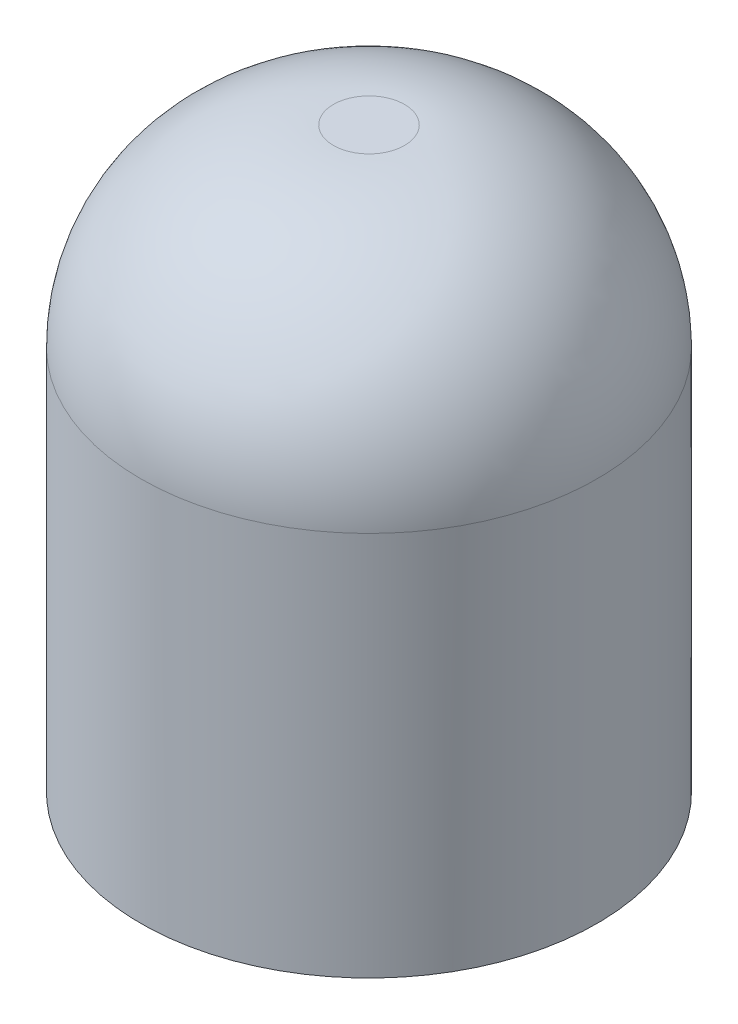
SolidWorks part; units mm, degrees
ref_plane "Front Plane" through (0, 0, 0) normal (0, 0, 1) x (1, 0, 0)
ref_plane "Top Plane" through (0, 0, 0) normal (0, 1, 0) x (1, 0, 0)
ref_plane "Right Plane" through (0, 0, 0) normal (1, 0, 0) x (0, 0, -1)
sketch "Sketch1" plane through (0, 0, 0) normal (0, 1, 0) x (1, 0, 0)
  circle A0 centre (0, 0) radius 30.0914
extrude "Boss-Extrude1" add sketch "Sketch1" along normal blind 76.2
fillet "Fillet2" radius 25.4 1 edges at (0, 76.2, 30.0914)
